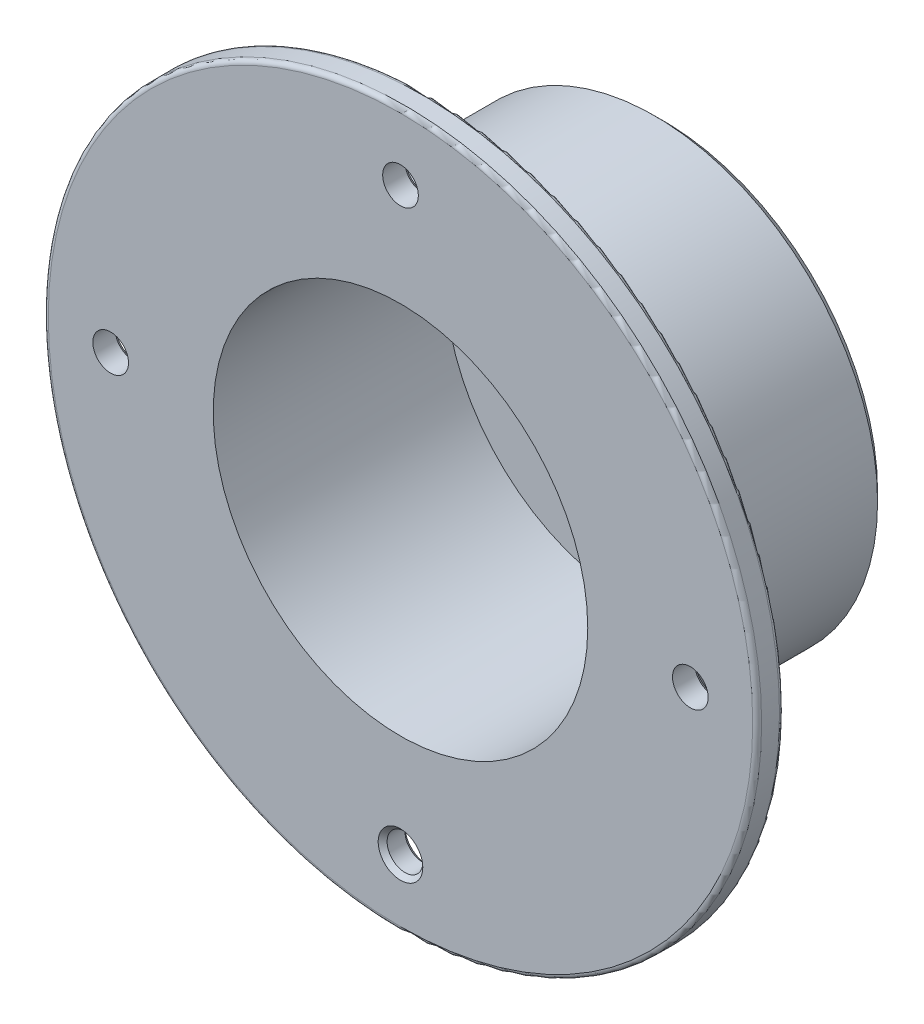
SolidWorks part; units mm, degrees
material "ABS"
ref_plane "Front Plane" through (0, 0, 0) normal (0, 0, 1) x (1, 0, 0)
ref_plane "Top Plane" through (0, 0, 0) normal (0, 1, 0) x (1, 0, 0)
ref_plane "Right Plane" through (0, 0, 0) normal (1, 0, 0) x (0, 0, -1)
sketch "Sketch1" plane through (0, 0, 0) normal (0, 0, 1) x (1, 0, 0)
  circle A0 centre (0, 0) radius 25
  dimension "D1" = 50
extrude "Boss-Extrude1" add sketch "Sketch1" along normal blind 29.5
sketch "Sketch2" plane through (0, 0, 29.5) normal (0, 0, 1) x (1, 0, 0)
  circle A0 centre (0, 0) radius 40
  circle A1 centre (0, 0) radius 25 construction
  dimension "D1" = 15
extrude "Boss-Extrude2" add sketch "Sketch2" against normal blind 3
chamfer "Chamfer1" distance 1 angle 45 2 edges at (25, 0, 26.5) (25, 0, 0)
sketch "Sketch3" plane through (0, 0, 29.5) normal (0, 0, 1) x (1, 0, 0)
  circle A0 centre (0, 0) radius 21
  circle A1 centre (0, 0) radius 24 construction
  dimension "D1" = 3
extrude "Cut-Extrude1" cut sketch "Sketch3" against normal blind 26
fillet "Fillet1" radius 0.5 2 edges at (40, 0, 26.5) (40, 0, 29.5)
sketch "Sketch4" plane through (0, 0, 26.5) normal (0, 0, -1) x (-1, 0, 0)
  line L0 (0, 32.5) -> (0, 0) construction
  circle A0 centre (0, 32.5) radius 2
  dimension "D1" = 4
  dimension "D2" = 32.5
extrude "Cut-Extrude2" cut sketch "Sketch4" against normal blind 26
pattern_circular "CirPattern1" count 4 over 360 about axis through (0, 0, 0) along (0, 0, 1) of "Cut-Extrude2"
chamfer "Chamfer2" distance 0.5 angle 45 5 edges at (2, -32.5, 26.5) (2, -32.5, 29.5) (32.5, 2, 26.5) (-32.5, -2, 26.5) (-2, 32.5, 26.5)
